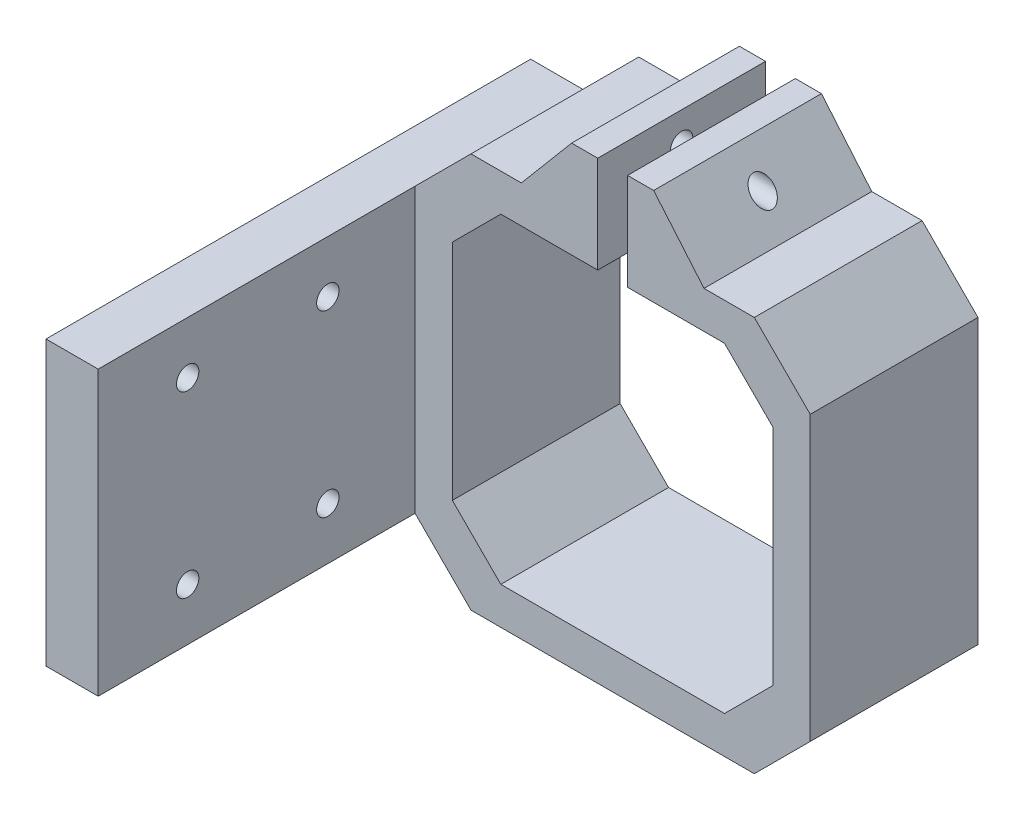
SolidWorks part; units mm, degrees
ref_plane "Alzado" through (0, 0, 0) normal (0, 0, 1) x (1, 0, 0)
ref_plane "Planta" through (0, 0, 0) normal (0, 1, 0) x (1, 0, 0)
ref_plane "Vista lateral" through (0, 0, 0) normal (1, 0, 0) x (0, 0, -1)
sketch "Croquis1" plane through (0, 0, 0) normal (0, 0, 1) x (1, 0, 0)
  line L0 (-15, 21.5) -> (-21.5, 15)
  line L1 (-21.5, 15) -> (-21.5, -15)
  line L2 (-21.5, -15) -> (-15, -21.5)
  line L3 (-15, -21.5) -> (15, -21.5)
  line L4 (15, -21.5) -> (21.5, -15)
  line L5 (21.5, -15) -> (21.5, 15)
  line L6 (21.5, 15) -> (15, 21.5)
  line L7 (15, 21.5) -> (2, 21.5)
  line L8 (-26.5, -19) -> (-26.5, 19)
  line L9 (-26.5, 19) -> (-19, 26.5)
  line L10 (-19, 26.5) -> (-12.25, 26.5)
  line L11 (19, 26.5) -> (26.5, 19)
  line L12 (26.5, 19) -> (26.5, -19)
  line L13 (26.5, -19) -> (19, -26.5)
  line L14 (19, -26.5) -> (-19, -26.5)
  line L15 (-19, -26.5) -> (-26.5, -19)
  line L16 (-12.25, 26.5) -> (-5.5, 34.5)
  line L17 (-5.5, 34.5) -> (-2, 34.5)
  line L18 (5.5, 34.5) -> (12.25, 26.5)
  line L19 (12.25, 26.5) -> (19, 26.5)
  line L21 (-2, 34.5) -> (-2, 21.5)
  line L22 (2, 34.5) -> (5.5, 34.5)
  line L23 (2, 34.5) -> (2, 21.5)
  line L24 (-2, 21.5) -> (-15, 21.5)
  dimension "D1" = 43
  dimension "D2" = 21.5
  dimension "D3" = 21.5
  dimension "D4" = 135
  dimension "D5" = 30
  dimension "D6" = 26.5
  dimension "D7" = 26.5
  dimension "D8" = 53
  dimension "D9" = 53
  dimension "D10" = 38
  dimension "D11" = 13
  dimension "D12" = 11
  dimension "D13" = 5.5
  dimension "D14" = 24.5
  dimension "D15" = 12.25
  dimension "D16" = 4
  dimension "D17" = 2
extrude "Saliente-Extruir1" add sketch "Croquis1" along normal blind 22.5
sketch "Croquis2" plane through (0, 0, 0) normal (0, 0, 1) x (1, 0, 0)
  line L1 (-26.5, 19) -> (-33.5, 19)
  line L2 (-26.5, 19) -> (-26.5, -19)
  line L3 (-26.5, -19) -> (-33.5, -19)
  line L4 (-33.5, 19) -> (-33.5, -19)
  dimension "D1" = 7
extrude "Saliente-Extruir2" add sketch "Croquis2" along normal blind 65
sketch "Croquis3" plane through (0, 0, 0) normal (1, 0, 0) x (0, 0, -1)
  line L0 (-65, -19) -> (-65, 19) construction
  line L1 (-65, 19) -> (-22.5, 19) construction
  line L8 (-22.5, 30.5) -> (0, 30.5) construction
  line L9 (-54.5, 13.5) -> (-32.7, 13.5) construction
  line L10 (-54.5, 13.5) -> (-54.5, -13.5) construction
  line L11 (-54.5, -13.5) -> (-32.7, -13.5) construction
  line L12 (-32.7, 13.5) -> (-32.7, -13.5) construction
  line L13 (-65, -19) -> (-22.5, -19) construction
  line L14 (0, -19) -> (0, 19) construction
  line L15 (-22.5, 26.5) -> (-22.5, 34.5) construction
  line L16 (0, 26.5) -> (0, 34.5) construction
  circle A0 centre (-11.25, 30.5) radius 1.5
  circle A1 centre (-53, 12) radius 1.5
  circle A2 centre (-34.2, 12) radius 1.5
  circle A3 centre (-34.2, -12) radius 1.5
  circle A4 centre (-53, -12) radius 1.5
  point P14 (-43.75, -19)
  dimension "D1" = 5.5
  dimension "D5" = 3
  dimension "D6" = 3
  dimension "D2" = 5.5
  dimension "D3" = 10.5
  dimension "D4" = 32.7
extrude "Cortar-Extruir1" cut sketch "Croquis3" against normal through all and the other way through all
